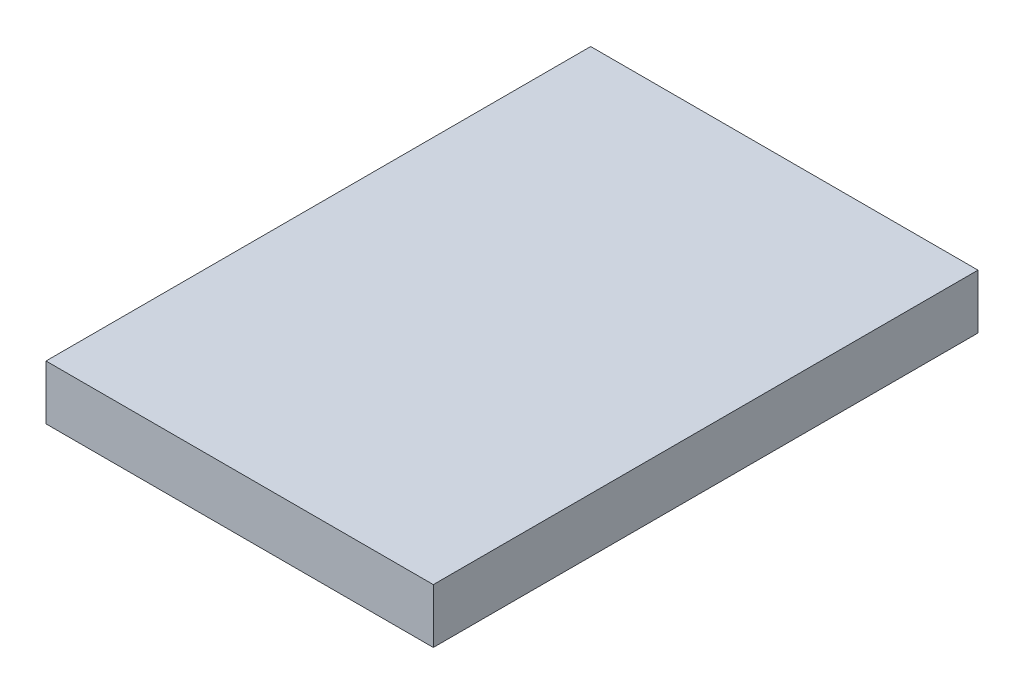
SolidWorks part; units mm, degrees
ref_plane "Front Plane" through (0, 0, 0) normal (0, 0, 1) x (1, 0, 0)
ref_plane "Top Plane" through (0, 0, 0) normal (0, 1, 0) x (1, 0, 0)
ref_plane "Right Plane" through (0, 0, 0) normal (1, 0, 0) x (0, 0, -1)
sketch "Sketch1" plane through (0, 0, 0) normal (0, 1, 0) x (1, 0, 0)
  line L0 (0, 0) -> (0, 4.5)
  line L1 (0, 4.5) -> (3.2, 4.5)
  line L2 (3.2, 4.5) -> (3.2, 0)
  line L3 (3.2, 0) -> (0, 0)
extrude "Boss-Extrude1" add sketch "Sketch1" along normal blind 0.45
